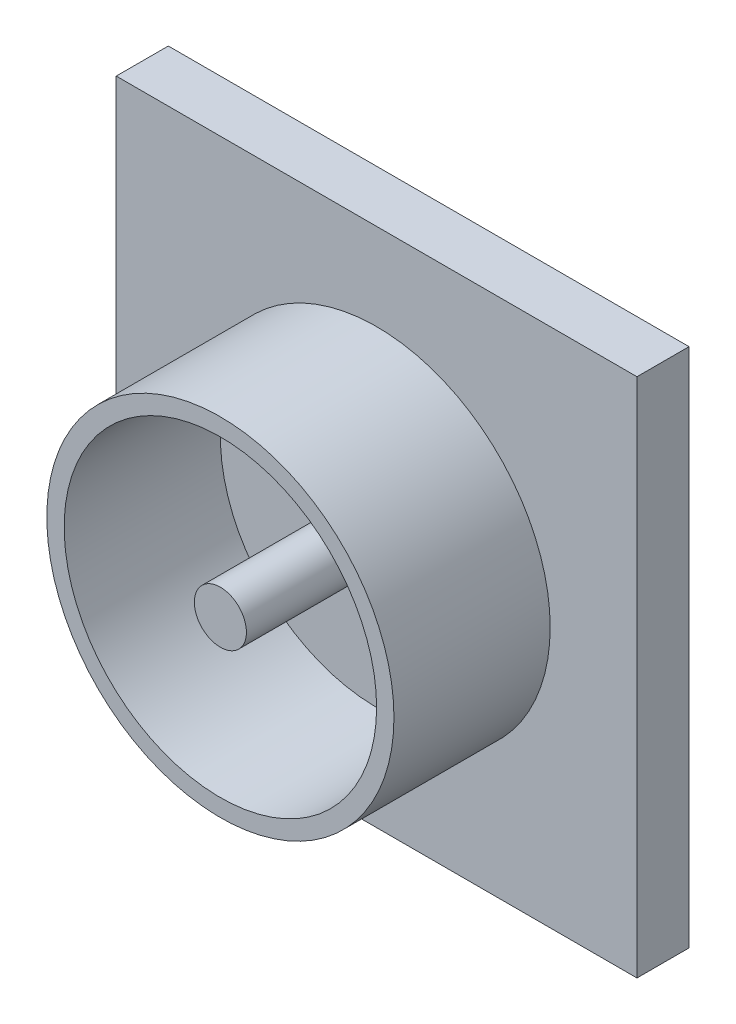
SolidWorks part; units mm, degrees
ref_plane "Alzado" through (0, 0, 0) normal (0, 0, 1) x (1, 0, 0)
ref_plane "Planta" through (0, 0, 0) normal (0, 1, 0) x (1, 0, 0)
ref_plane "Vista lateral" through (0, 0, 0) normal (1, 0, 0) x (0, 0, -1)
sketch "Croquis1" plane through (0, 0, 0) normal (0, 0, 1) x (1, 0, 0)
  line L1 (1.5, -1.5) -> (-1.5, -1.5)
  line L2 (1.5, -1.5) -> (1.5, 1.5)
  line L3 (1.5, 1.5) -> (-1.5, 1.5)
  line L4 (-1.5, -1.5) -> (-1.5, 1.5)
  line L5 (1.5, -1.5) -> (-1.5, 1.5) construction
  line L6 (1.5, 1.5) -> (-1.5, -1.5) construction
  point P0 (0, 0)
  dimension "D1" = 3
extrude "Saliente-Extruir1" add sketch "Croquis1" along normal blind 0.3
sketch "Croquis2" plane through (0, 0, 0.3) normal (0, 0, 1) x (1, 0, 0)
  circle A0 centre (0, 0) radius 1
  circle A1 centre (0, 0) radius 0.9
  circle A2 centre (0, 0) radius 0.15
  dimension "D1" = 2
  dimension "D3" = 0.3
  dimension "D2" = 0.1
extrude "Saliente-Extruir2" add sketch "Croquis2" along normal blind 0.9 contours A0 A1 | A2
